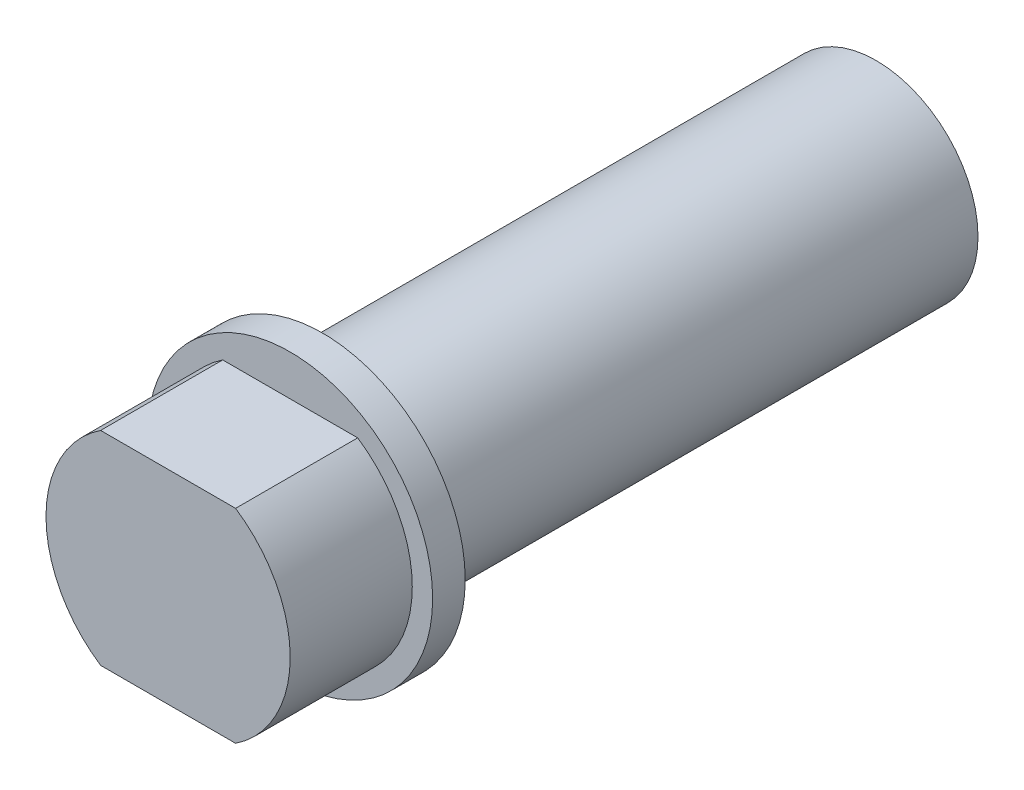
SolidWorks part; units mm, degrees
ref_plane "Front Plane" through (0, 0, 0) normal (0, 0, 1) x (1, 0, 0)
ref_plane "Top Plane" through (0, 0, 0) normal (0, 1, 0) x (1, 0, 0)
ref_plane "Right Plane" through (0, 0, 0) normal (1, 0, 0) x (0, 0, -1)
sketch "Sketch1" plane through (0, 0, 0) normal (0, 0, 1) x (1, 0, 0)
  circle A0 centre (0, 0) radius 12.5
extrude "Shaft_D25x68" add sketch "Sketch1" along normal blind 68
ref_plane "Plane_Collar_68mm" through (0, 0, 68) normal (0, 0, 1) x (1, 0, 0)
sketch "Sketch2" plane through (0, 0, 68) normal (0, 0, 1) x (1, 0, 0)
  circle A0 centre (0, 0) radius 17.5
extrude "Collar_D35x4" add sketch "Sketch2" along normal blind 4
ref_plane "Plane_Seat_72mm" through (0, 0, 72) normal (0, 0, 1) x (1, 0, 0)
sketch "Sketch3" plane through (0, 0, 72) normal (0, 0, 1) x (1, 0, 0)
  circle A0 centre (0, 0) radius 15
extrude "GearD_Seat_D30x15" add sketch "Sketch3" along normal blind 15
sketch "Sketch4" plane through (0, 0, 72) normal (0, 0, 1) x (1, 0, 0)
  line L1 (-16, 12.5) -> (16, 12.5)
  line L2 (-16, 12.5) -> (-16, 16)
  line L3 (-16, 16) -> (16, 16)
  line L4 (16, 12.5) -> (16, 16)
  line L6 (-16, -12.5) -> (16, -12.5)
  line L7 (-16, -12.5) -> (-16, -16)
  line L8 (-16, -16) -> (16, -16)
  line L9 (16, -12.5) -> (16, -16)
extrude "Double_Flat_Cut_25mm" cut sketch "Sketch4" along normal blind 15
sketch "Sketch5" plane through (0, 0, 0) normal (1, 0, 0) x (0, 0, -1)
  line L0 (-90, 0) -> (10, 0) construction
  line L2 (-65, 11.5) -> (-66, 11.5)
  line L3 (-65, 11.5) -> (-65, 13.5)
  line L4 (-65, 13.5) -> (-66, 13.5)
  line L5 (-66, 11.5) -> (-66, 13.5)
revolve "SnapRing_Groove_D23x1" cut sketch "Sketch5" angle 360 about L0
